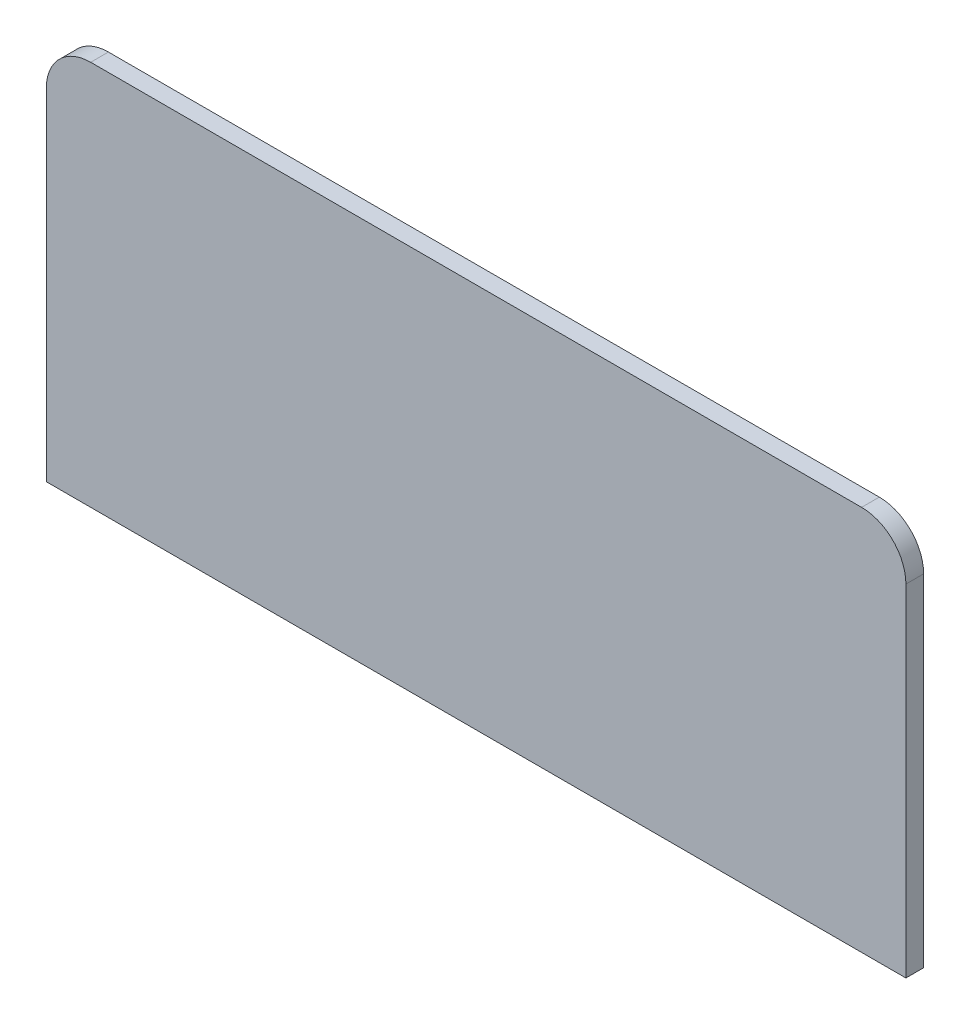
SolidWorks part; units mm, degrees
ref_plane "前视基准面" through (0, 0, 0) normal (0, 0, 1) x (1, 0, 0)
ref_plane "上视基准面" through (0, 0, 0) normal (0, 1, 0) x (1, 0, 0)
ref_plane "右视基准面" through (0, 0, 0) normal (1, 0, 0) x (0, 0, -1)
other "Configuration Table"
sketch "草图1" plane through (0, 0, 0) normal (0, 0, 1) x (1, 0, 0)
  line L1 (-97, -43.5) -> (97, -43.5)
  line L2 (-97, -43.5) -> (-97, 43.5)
  line L3 (-97, 43.5) -> (97, 43.5)
  line L4 (97, -43.5) -> (97, 43.5)
  line L5 (-97, -43.5) -> (97, 43.5) construction
  line L6 (-97, 43.5) -> (97, -43.5) construction
  point P0 (0, 0)
  dimension "D1" = 194
  dimension "D2" = 87
extrude "凸台-拉伸1" add sketch "草图1" along normal blind 4
fillet "圆角1" radius 10 2 edges at (-97, 43.5, 2) (97, 43.5, 2)
